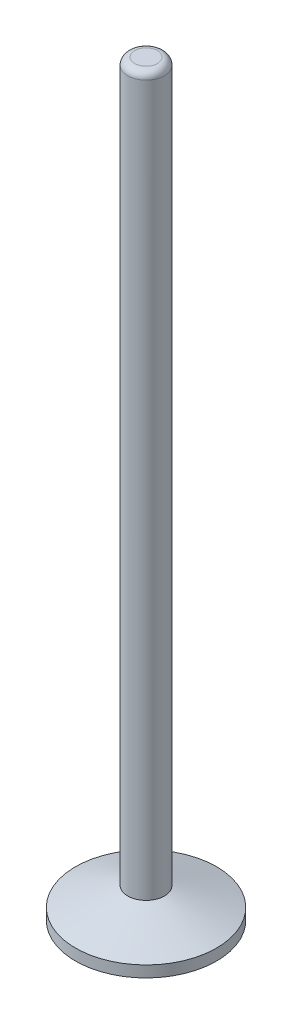
SolidWorks part; units mm, degrees
ref_plane "Plan de face" through (0, 0, 0) normal (0, 0, 1) x (1, 0, 0)
ref_plane "Plan de dessus" through (0, 0, 0) normal (0, 1, 0) x (1, 0, 0)
ref_plane "Plan de droite" through (0, 0, 0) normal (1, 0, 0) x (0, 0, -1)
sketch "Esquisse2" plane through (0, 0, 0) normal (0, 0, 1) x (1, 0, 0)
  line L0 (0, 0) -> (0, 530)
  line L1 (0, 530) -> (13, 530)
  line L2 (13, 530) -> (13, 21.4669)
  line L3 (13, 21.4669) -> (50, 8)
  line L4 (50, 8) -> (50, 0)
  line L5 (50, 0) -> (0, 0)
  dimension "D1" = 13
  dimension "D2" = 530
  dimension "D3" = 50
  dimension "D4" = 20
  dimension "D5" = 8
revolve "Révolution1" add sketch "Esquisse2" angle 360 about L0
fillet "Congé1" radius 5 1 edges at (0, 530, -13)
